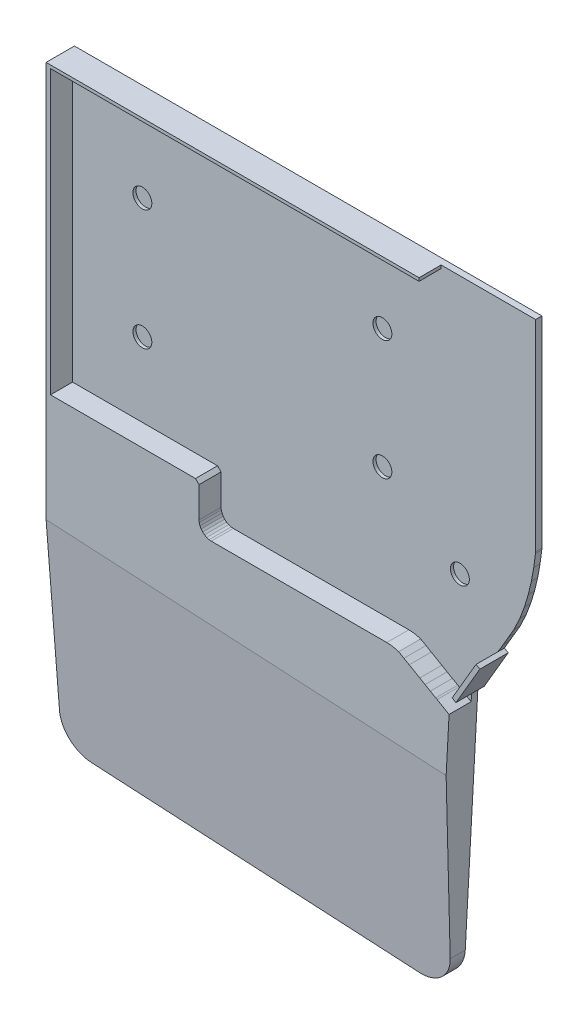
SolidWorks part; units mm, degrees
ref_plane "前视基准面" through (0, 0, 0) normal (0, 0, 1) x (1, 0, 0)
ref_plane "上视基准面" through (0, 0, 0) normal (0, 1, 0) x (1, 0, 0)
ref_plane "右视基准面" through (0, 0, 0) normal (1, 0, 0) x (0, 0, -1)
other "Configuration Table"
sketch "草图1" plane through (0, 0, 0) normal (0, 0, 1) x (1, 0, 0)
  line L1 (-73.5, 97) -> (73.5, 97)
  line L2 (-73.5, 97) -> (-73.5, -97)
  line L3 (-73.5, -97) -> (73.5, -97)
  line L4 (73.5, 97) -> (73.5, -97)
  line L5 (-73.5, 97) -> (73.5, -97) construction
  line L6 (-73.5, -97) -> (73.5, 97) construction
  point P0 (0, 0)
  dimension "D1" = 147
  dimension "D2" = 194
extrude "凸台-拉伸1" add sketch "草图1" along normal blind 2
sketch "草图3" plane through (0, 0, 2) normal (0, 0, 1) x (1, 0, 0)
  line L0 (53.2352, -12.0676) -> (54.8955, -9.2276) construction
  line L1 (54.8955, -9.2276) -> (56.5712, -6.3612) construction
  line L2 (56.5712, -6.3612) -> (59.9226, -0.6286) construction
  line L3 (59.9226, -0.6286) -> (61.5982, 2.2377) construction
  line L4 (61.5982, 2.2377) -> (63.2739, 5.104) construction
  line L5 (64.9496, 7.9704) -> (66.6853, 10.9393) construction
  line L6 (63.2739, 5.104) -> (64.9496, 7.9704) construction
  line L7 (66.6853, 10.9393) -> (68.4749, 14.8005) construction
  line L8 (68.4749, 14.8005) -> (69.9655, 18.7518) construction
  line L9 (69.9655, 18.7518) -> (71.1866, 22.7855) construction
  line L10 (71.1866, 22.7855) -> (72.1607, 26.8788) construction
  line L11 (72.1607, 26.8788) -> (72.9097, 31.0097) construction
  line L12 (72.9097, 31.0097) -> (73.4554, 35.1566) construction
  line L13 (73.4554, 35.1566) -> (73.8189, 39.2984) construction
  line L14 (73.8189, 39.2984) -> (74.0225, 43.4331) construction
  line L15 (74.0225, 43.4331) -> (74.0225, 45) construction
  line L16 (53.2352, -12.0676) -> (54.8955, -9.2276)
  line L17 (54.8955, -9.2276) -> (56.5712, -6.3612)
  line L18 (56.5712, -6.3612) -> (59.9226, -0.6286)
  line L19 (59.9226, -0.6286) -> (61.5982, 2.2377)
  line L20 (61.5982, 2.2377) -> (63.2739, 5.104)
  line L21 (64.9496, 7.9704) -> (66.6853, 10.9393)
  line L22 (63.2739, 5.104) -> (64.9496, 7.9704)
  line L23 (66.6853, 10.9393) -> (68.4749, 14.8005)
  line L24 (68.4749, 14.8005) -> (69.9655, 18.7518)
  line L25 (69.9655, 18.7518) -> (71.1866, 22.7855)
  line L26 (71.1866, 22.7855) -> (72.1607, 26.8788)
  line L27 (72.1607, 26.8788) -> (72.9097, 31.0097)
  line L28 (72.9097, 31.0097) -> (73.4554, 35.1566)
  line L29 (73.4554, 35.1566) -> (73.8189, 39.2984)
  line L30 (73.8189, 39.2984) -> (74.0225, 43.4331)
  line L31 (74.0225, 43.4331) -> (74.0225, 45)
  line L32 (53.2352, -12.0676) -> (48.2042, -104.8197)
  line L33 (48.2042, -104.8197) -> (75.7231, -104.8197)
  line L34 (75.7231, -104.8197) -> (75.7231, 45)
  line L35 (75.7231, 45) -> (74.0225, 45)
extrude "切除-拉伸1" cut sketch "草图3" against normal through all
sketch "草图4" plane through (0, 0, 2) normal (0, 0, 1) x (1, 0, 0)
  line L0 (-26.3593, 7.6715) -> (-26.3593, -2.0502) construction
  line L1 (48.8087, -13.3822) -> (49.2397, -13.6017) construction
  line L2 (47.0749, -12.3783) -> (48.8087, -13.3822) construction
  line L3 (45.3993, -11.4082) -> (47.0749, -12.3783) construction
  line L4 (43.7236, -10.438) -> (45.3993, -11.4082) construction
  line L5 (40.3722, -8.4979) -> (43.7236, -10.438) construction
  line L6 (38.6965, -7.5276) -> (40.3722, -8.4979) construction
  line L7 (37.0216, -6.558) -> (38.6965, -7.5276) construction
  line L8 (-22.485, -5.9249) -> (33.2585, -5.9249) construction
  line L9 (-69.6253, 8.7971) -> (-27.4849, 8.7971) construction
  line L10 (-26.3593, 7.6715) -> (-26.3593, -2.0502)
  line L11 (48.8087, -13.3822) -> (49.2397, -13.6017)
  line L12 (47.0749, -12.3783) -> (48.8087, -13.3822)
  line L13 (45.3993, -11.4082) -> (47.0749, -12.3783)
  line L14 (43.7236, -10.438) -> (45.3993, -11.4082)
  line L15 (40.3722, -8.4979) -> (43.7236, -10.438)
  line L16 (38.6965, -7.5276) -> (40.3722, -8.4979)
  line L17 (37.0216, -6.558) -> (38.6965, -7.5276)
  line L18 (-22.485, -5.9249) -> (33.2585, -5.9249)
  line L19 (-69.6253, 8.7971) -> (-27.4849, 8.7971)
  line L20 (-69.6253, 8.7971) -> (-73.5, 8.7971)
  line L21 (-73.5, 97) -> (-73.5, -97) construction
  line L22 (-73.5, 8.7971) -> (-73.5, -97)
  line L23 (-73.5, -97) -> (48.6284, -97)
  line L24 (48.6284, -97) -> (53.0324, -15.806)
  line L25 (53.2352, -12.0676) -> (48.6284, -97) construction
  line L26 (53.0324, -15.806) -> (49.2397, -13.6017)
  line L27 (-26.3593, 7.6715) -> (-27.4849, 8.7971)
  line L28 (-23.1622, -5.8566) -> (-22.485, -5.9249) construction
  line L29 (-23.9188, -5.6221) -> (-23.1622, -5.8566) construction
  line L30 (-24.6026, -5.2513) -> (-23.9188, -5.6221) construction
  line L31 (-25.1964, -4.7615) -> (-24.6026, -5.2513) construction
  line L32 (-25.6856, -4.1681) -> (-25.1964, -4.7615) construction
  line L33 (-26.0565, -3.4847) -> (-25.6856, -4.1681) construction
  line L34 (-26.2912, -2.7273) -> (-26.0565, -3.4847) construction
  line L35 (-26.3593, -2.0502) -> (-26.2912, -2.7273) construction
  line L36 (-23.1622, -5.8566) -> (-22.485, -5.9249)
  line L37 (-23.9188, -5.6221) -> (-23.1622, -5.8566)
  line L38 (-24.6026, -5.2513) -> (-23.9188, -5.6221)
  line L39 (-25.1964, -4.7615) -> (-24.6026, -5.2513)
  line L40 (-25.6856, -4.1681) -> (-25.1964, -4.7615)
  line L41 (-26.0565, -3.4847) -> (-25.6856, -4.1681)
  line L42 (-26.2912, -2.7273) -> (-26.0565, -3.4847)
  line L43 (-26.3593, -2.0502) -> (-26.2912, -2.7273)
  arc A0 (37.0216, -6.558) -> (33.2585, -5.9249) centre (33.2585, -17.4249) ccw construction
  arc A1 (37.0216, -6.558) -> (33.2585, -5.9249) centre (33.2585, -17.4249) ccw
extrude "凸台-拉伸2" add sketch "草图4" along normal blind 7
sketch "草图6" plane through (0, 0, 0) normal (0, 0, -1) x (-1, 0, 0)
  line L0 (-61.5982, 2.2377) -> (-53.9983, -10.7623)
  line L1 (-73.5, 97) -> (73.5, 97)
  line L2 (-73.5, 97) -> (-73.5, 99.5)
  line L3 (-73.5, 99.5) -> (74.9, 99.5)
  line L4 (74.9, 87) -> (74.9, 99.5)
  line L5 (73.5, -97) -> (74.9, -97)
  line L6 (73.5, -97) -> (73.5, 97)
  line L8 (74.9, -97) -> (74.9, 87)
  line L9 (-54.8955, -9.2276) -> (-53.2352, -12.0676) construction
  line L10 (-53.9983, -10.7623) -> (-55.2069, -11.4689)
  line L11 (-55.2069, -11.4689) -> (-62.8069, 1.5311)
  line L12 (-62.8069, 1.5311) -> (-61.5982, 2.2377)
  dimension "D1" = 2.5
  dimension "D2" = 1.4
  dimension "D3" = 1.4
  dimension "D4" = 13
extrude "凸台-拉伸12" add sketch "草图6" against normal blind 2
sketch "草图7" plane through (0, 0, 2) normal (0, 0, 1) x (1, 0, 0)
  line L0 (73.5, 35.6649) -> (73.5, 99.5) construction
  line L2 (-74.9, 99.5) -> (-74.9, -97)
  line L3 (-74.9, -97) -> (-73.5, -97)
  line L4 (-73.5, 98.5) -> (-73.5, -97)
  line L8 (73.5, 99.5) -> (73.5, 98.5)
  line L9 (61.5982, 2.2377) -> (53.9983, -10.7623)
  line L10 (53.9983, -10.7623) -> (55.2069, -11.4689)
  line L11 (55.2069, -11.4689) -> (62.8069, 1.5311)
  line L12 (62.8069, 1.5311) -> (61.5982, 2.2377)
  line L14 (-74.9, 99.5) -> (73.5, 99.5)
  line L15 (73.5, 98.5) -> (-73.5, 98.5)
  dimension "D1" = 1
extrude "凸台-拉伸13" add sketch "草图7" along normal blind 7
sketch "草图17" plane through (0, 0, 9) normal (0, 0, 1) x (1, 0, 0)
  line L1 (-73.5, 8.7971) -> (-74.9, 8.7971)
  line L2 (-73.5, 8.7971) -> (-73.5, -97)
  line L3 (-73.5, -97) -> (-74.9, -97)
  line L4 (-74.9, 8.7971) -> (-74.9, -97)
extrude "凸台-拉伸14" [suppressed] add sketch "草图17" along normal blind 5
sketch "草图9" plane through (0, 99.5, 0) normal (0, 1, 0) x (1, 0, 0)
  line L5 (73.5, -9) -> (43.5, -9)
  line L6 (73.5, -9) -> (73.5, -2)
  line L7 (73.5, -2) -> (43.5, -2)
  line L8 (43.5, -9) -> (43.5, -2)
  dimension "D1" = 7
  dimension "D2" = 30
extrude "切除-拉伸2" cut sketch "草图9" against normal blind 8
sketch "草图10" plane through (53.7317, -2.9145, 0) normal (0.9985, -0.0542, 0) x (0, 0, -1)
  line L0 (-9, -30.2238) -> (-4, -94.2238)
  line L1 (-9, -94.2238) -> (-9, -12.9105) construction
  line L2 (0, -94.2238) -> (-9, -94.2238) construction
  line L3 (-9, -30.2238) -> (-9, -94.2238)
  line L7 (-9, -94.2238) -> (-9, -111.5148)
  line L8 (-9, -111.5148) -> (-4, -111.5148)
  line L9 (-4, -94.2238) -> (-4, -111.5148)
  dimension "D1" = 5
  dimension "D2" = 64
extrude "切除-拉伸3" cut sketch "草图10" against normal through all
sketch "草图11" plane through (0, 0, 4) normal (0, 0, 1) x (1, 0, 0)
  line L0 (-74.9, -90.2996) -> (-74.9, -97)
  line L1 (-74.9, -97) -> (48.6284, -97)
  line L2 (48.6284, -97) -> (-74.9, -90.2996)
extrude "切除-拉伸4" cut sketch "草图11" against normal through all
fillet "圆角1" radius 10 2 edges at (48.6284, -97, 2) (-74.9, -90.2996, 2)
sketch "草图15" plane through (0, 0, 2) normal (0, 0, 1) x (1, 0, 0)
  line L0 (-73.5, 98.5) -> (43.5, 98.5) construction
  line L1 (-73.5, 8.7971) -> (-73.5, 98.5) construction
  circle A0 centre (-51.34, 70.5) radius 3
  circle A1 centre (-51.34, 32.3) radius 3
  circle A2 centre (24.86, 72.7) radius 3
  circle A3 centre (24.86, 34.7) radius 3
  circle A4 centre (49.46, 17.5) radius 3
  dimension "D1" = 6
  dimension "D2" = 28
  dimension "D3" = 76.2
  dimension "D4" = 76.2
  dimension "D5" = 38.2
  dimension "D6" = 38
  dimension "D7" = 24.6
  dimension "D8" = 122.96
  dimension "D9" = 22.16
  dimension "D10" = 22.16
  dimension "D11" = 25.8
  dimension "D12" = 81
extrude "切除-拉伸5" cut sketch "草图15" against normal blind 1
